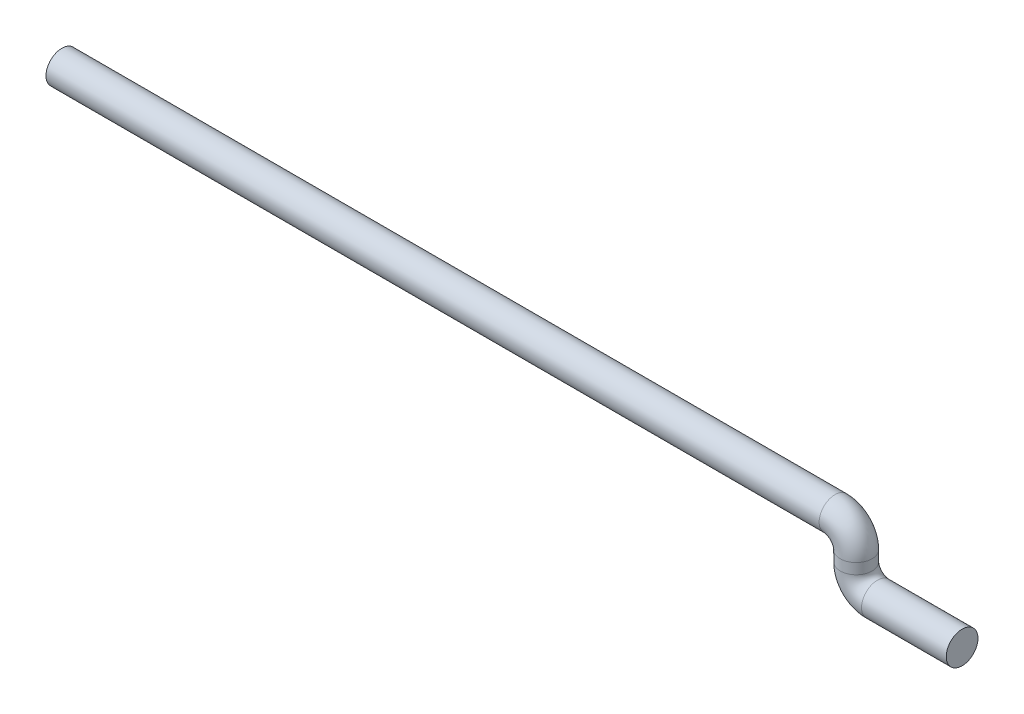
SolidWorks part; units mm, degrees
ref_plane "Front Plane" through (0, 0, 0) normal (0, 0, 1) x (1, 0, 0)
ref_plane "Top Plane" through (0, 0, 0) normal (0, 1, 0) x (1, 0, 0)
ref_plane "Right Plane" through (0, 0, 0) normal (1, 0, 0) x (0, 0, -1)
sketch "Sketch1" plane through (0, 0, 0) normal (1, 0, 0) x (0, 0, -1)
  circle A0 centre (0, 0) radius 0.762
  dimension ".06" = 1.524
sketch "Sketch2" plane through (0, 0, 0) normal (0, 0, 1) x (1, 0, 0)
  line L0 (0, 0) -> (37.084, 0)
  line L1 (38.1, -1.016) -> (38.1, -1.524)
  line L2 (39.116, -2.54) -> (43.18, -2.54)
  arc A0 (38.1, -1.524) -> (39.116, -2.54) centre (39.116, -1.524) ccw
  arc A1 (37.084, 0) -> (38.1, -1.016) centre (37.084, -1.016) cw
  point P7 (38.1, -2.54)
  point P10 (38.1, 0)
  dimension "D2" = 1.016
  dimension "D1" = 2.54
  dimension "1.5" = 38.1
  dimension ".2" = 5.08
sweep "Sweep2" add profiles "Sketch1" path "Sketch2"
